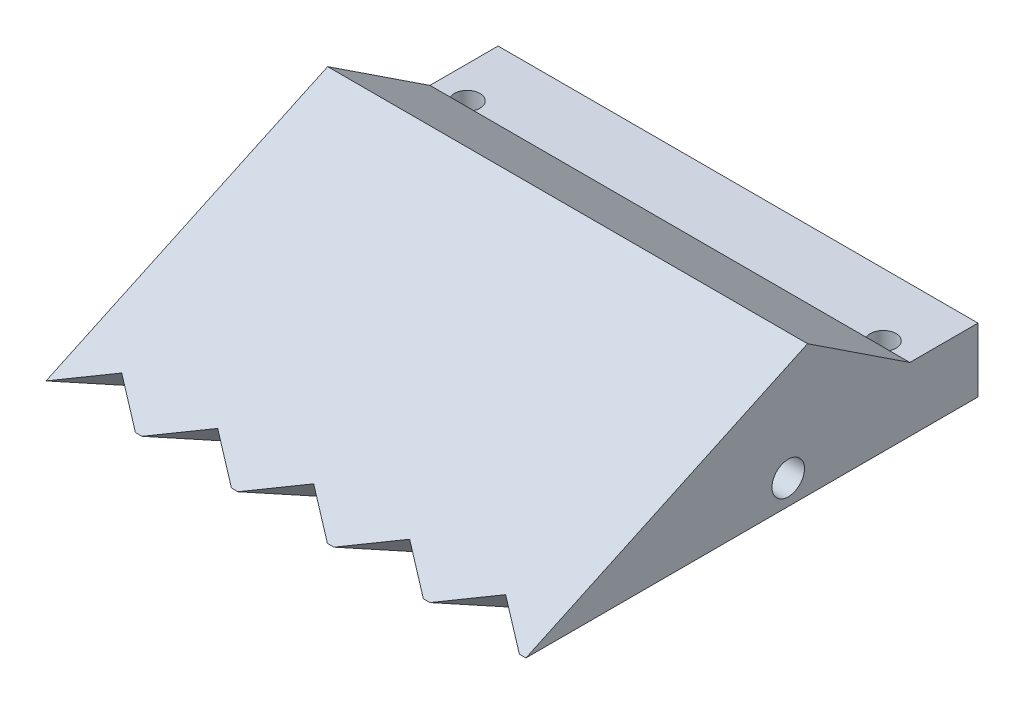
SolidWorks part; units mm, degrees
ref_plane "Front Plane" through (0, 0, 0) normal (0, 0, 1) x (1, 0, 0)
ref_plane "Top Plane" through (0, 0, 0) normal (0, 1, 0) x (1, 0, 0)
ref_plane "Right Plane" through (0, 0, 0) normal (1, 0, 0) x (0, 0, -1)
sketch "Sketch1" plane through (0, 0, 0) normal (1, 0, 0) x (0, 0, -1)
  line L0 (-35.4476, 4.1732) -> (35.2065, 4.1732)
  line L1 (35.2065, 4.1732) -> (35.2065, 14.1732)
  line L2 (35.2065, 14.1732) -> (24.5524, 14.1732)
  line L3 (24.5524, 14.1732) -> (8.5711, 24.6994)
  line L4 (8.5711, 24.6994) -> (-35.4476, 4.1732)
  dimension "D1" = 25
  dimension "D2" = 10
  dimension "D3" = 60
extrude "Boss-Extrude1" add sketch "Sketch1" along normal blind 75
sketch "Sketch2" plane through (0, 14.1732, 0) normal (0, 1, 0) x (1, 0, 0)
  line L0 (0, -11.2894) -> (0, 11.2894) construction
  circle A0 centre (5, 25.3746) radius 2
  circle A1 centre (70, 25.3865) radius 2
  dimension "D1" = 4
  dimension "D2" = 4
  dimension "D3" = 65
  dimension "D4" = 5
extrude "Cut-Extrude1" cut sketch "Sketch2" against normal blind 10
sketch "Sketch3" plane through (0, 0, 0) normal (-1, 0, 0) x (0, 0, 1)
  circle A0 centre (-5.5476, 8.0335) radius 2.543
sketch "Sketch4" plane through (0, 17.0051, 7.9296) normal (0, 0.9063, 0.4226) x (1, 0, 0)
  line L0 (0, -30.3628) -> (7.0659, -25.1031)
  line L1 (0, -11.2894) -> (0, 11.2894) construction
  line L2 (75, -30.3628) -> (0, -30.3628) construction
  line L3 (7.0659, -25.1031) -> (13.9766, -30.3628)
  line L4 (22.0659, -25.1031) -> (28.9766, -30.3628)
  line L5 (15, -30.3628) -> (22.0659, -25.1031)
  line L6 (37.0659, -25.1031) -> (43.9766, -30.3628)
  line L7 (30, -30.3628) -> (37.0659, -25.1031)
  line L8 (52.0659, -25.1031) -> (58.9766, -30.3628)
  line L9 (45, -30.3628) -> (52.0659, -25.1031)
  line L10 (67.0659, -25.1031) -> (73.9766, -30.3628)
  line L11 (60, -30.3628) -> (67.0659, -25.1031)
  line L12 (13.9766, -30.3628) -> (0, -30.3628)
  line L13 (15, -30.3628) -> (28.9766, -30.3628)
  line L14 (43.9766, -30.3628) -> (30, -30.3628)
  line L15 (45, -30.3628) -> (58.9766, -30.3628)
  line L16 (73.9766, -30.3628) -> (60, -30.3628)
  dimension "D1" = 5
extrude "Cut-Extrude2" cut sketch "Sketch4" against normal blind 10
extrude "Cut-Extrude3" cut sketch "Sketch3" against normal blind 100 contours A0
chamfer "Chamfer1" distance 2 angle 45 2 edges at (70, 4.1732, -23.3865) (5, 4.1732, -23.3746)
